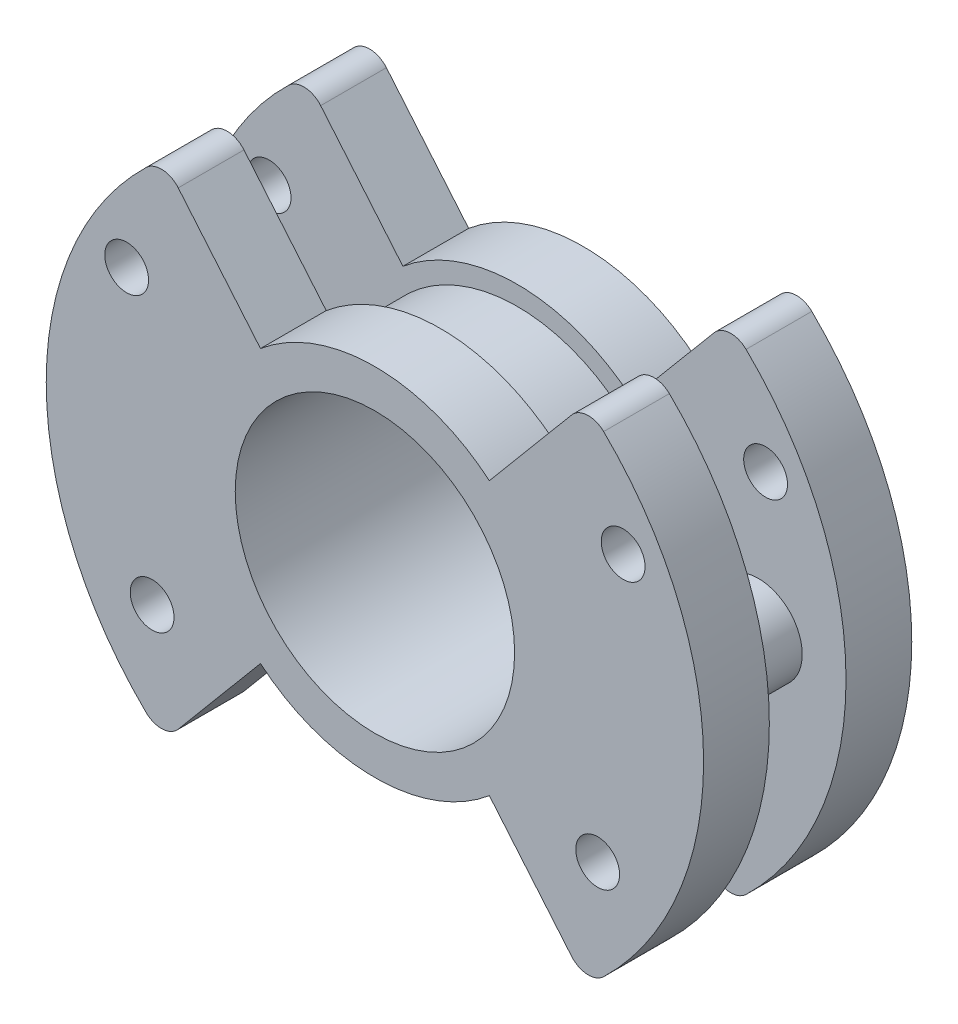
SolidWorks part; units mm, degrees
ref_plane "Front Plane" through (0, 0, 0) normal (0, 0, 1) x (1, 0, 0)
ref_plane "Top Plane" through (0, 0, 0) normal (0, 1, 0) x (1, 0, 0)
ref_plane "Right Plane" through (0, 0, 0) normal (1, 0, 0) x (0, 0, -1)
sketch "Sketch1" plane through (0, 0, 0) normal (0, 0, 1) x (1, 0, 0)
  circle A0 centre (0, 0) radius 30
  dimension "D1" = 60
extrude "Boss-Extrude1" add sketch "Sketch1" against normal blind 6
sketch "Sketch2" plane through (0, 0, 0) normal (0, 0, 1) x (1, 0, 0)
  circle A0 centre (0, 0) radius 14.5
  dimension "D1" = 29
extrude "Boss-Extrude2" add sketch "Sketch2" along normal blind 13
sketch "Sketch3" plane through (0, 0, 13) normal (0, 0, 1) x (1, 0, 0)
  circle A0 centre (0, 0) radius 12.75
  dimension "D1" = 25.5
extrude "Cut-Extrude1" cut sketch "Sketch3" against normal through all both and the other way through all
sketch "Sketch5" plane through (0, 0, 0) normal (0, 0, 1) x (1, 0, 0)
  circle A0 centre (0, 0) radius 30
  circle A1 centre (0, 0) radius 12.75
  circle A2 centre (0, 0) radius 12.75 construction
  circle A3 centre (0, 0) radius 30 construction
extrude "Boss-Extrude4" add sketch "Sketch5" against normal blind 6 from surface at 13 starting at face at (12.75, 0, 13)
sketch "Sketch6" plane through (0, 0, 0) normal (0, 0, 1) x (1, 0, 0)
  line L0 (-30, 0) -> (0, 0) construction
  line L1 (0, -41.069) -> (0, 41.069) construction
  line L2 (-40.6561, -12.75) -> (0, -12.75) construction
  line L3 (-20.3332, 0) -> (-20.3332, -41.5595) construction
  line L4 (-22.6592, 0) -> (-22.6592, 41.4208) construction
  line L6 (-40.6561, 12.75) -> (0, 12.75) construction
  circle A0 centre (0, 0) radius 12.75 construction
  circle A1 centre (-20.3332, -12.75) radius 2
  circle A2 centre (0, 0) radius 30 construction
  circle A4 centre (-22.6592, 12.75) radius 2
  circle A7 centre (20.3332, -12.75) radius 2
  circle A10 centre (22.6592, 12.75) radius 2
  dimension "D1" = 4
  dimension "D2" = 24
  dimension "D5" = 4
  dimension "D4" = 26
extrude "Cut-Extrude2" cut sketch "Sketch6" against normal through all both and the other way through all
sketch "Sketch7" plane through (0, 0, 13) normal (0, 0, 1) x (1, 0, 0)
  line L0 (0, 0) -> (-12.75, 0) construction
  line L1 (0, 0) -> (0, 12.75) construction
  line L2 (0, 0) -> (-27.5333, -32.8129) construction
  line L3 (0, 0) -> (27.5333, -32.8129) construction
  line L4 (10.4453, -12.4482) -> (19.2836, -22.9813)
  line L5 (-10.4453, 12.4482) -> (-19.2836, 22.9813)
  line L6 (-10.4453, -12.4482) -> (-19.2836, -22.9813)
  line L7 (10.4453, 12.4482) -> (19.2836, 22.9813)
  arc A0 (-10.4453, 12.4482) -> (10.4453, 12.4482) centre (0, 0) cw
  arc A1 (-19.2836, 22.9813) -> (19.2836, 22.9813) centre (0, 0) cw
  circle A4 centre (0, 0) radius 12.75 construction
  circle A5 centre (0, 0) radius 30 construction
  arc A6 (-10.4453, -12.4482) -> (10.4453, -12.4482) centre (0, 0) ccw
  arc A7 (-19.2836, -22.9813) -> (19.2836, -22.9813) centre (0, 0) ccw
  dimension "D2" = 3.5
  dimension "D1" = 50
  dimension "D3" = 50
extrude "Cut-Extrude3" cut sketch "Sketch7" against normal through all both and the other way through all
fillet "Fillet1" radius 2 1 edges at (-19.2836, -22.9813, 10)
fillet "Fillet2" radius 2 1 edges at (-19.2836, 22.9813, 10)
fillet "Fillet3" radius 2 1 edges at (19.2836, 22.9813, 10)
fillet "Fillet4" radius 2 1 edges at (19.2836, -22.9813, 10)
sketch "Sketch8" plane through (0, 0, 13) normal (0, 0, 1) x (1, 0, 0)
  line L0 (0, 42.8702) -> (0, -42.8702) construction
  line L1 (-42.07, 0) -> (42.07, 0) construction
  circle A9 centre (-22, 0) radius 4
  circle A11 centre (22, 0) radius 4
  dimension "D6" = 8
  dimension "D7" = 22
extrude "Boss-Extrude5" add sketch "Sketch8" against normal up to surface (13 mm away) up to face at (0, 0, 0)
fillet "Fillet5" radius 2 1 edges at (-19.2836, 22.9813, -3)
fillet "Fillet6" radius 2 1 edges at (-19.2836, -22.9813, -3)
fillet "Fillet7" radius 2 1 edges at (19.2836, -22.9813, -3)
fillet "Fillet8" radius 2 1 edges at (19.2836, 22.9813, -3)
sketch "Sketch10" plane through (0, 0, 13) normal (0, 0, 1) x (1, 0, 0)
  line L0 (0, 23.4531) -> (0, -27.6078) construction
  line L1 (-33.7286, -30) -> (35, -30) construction
  line L2 (-33.7286, -12.75) -> (35, -12.75) construction
  arc A1 (-20.8759, 21.5452) -> (-20.8759, -21.5452) centre (0, 0) ccw construction
